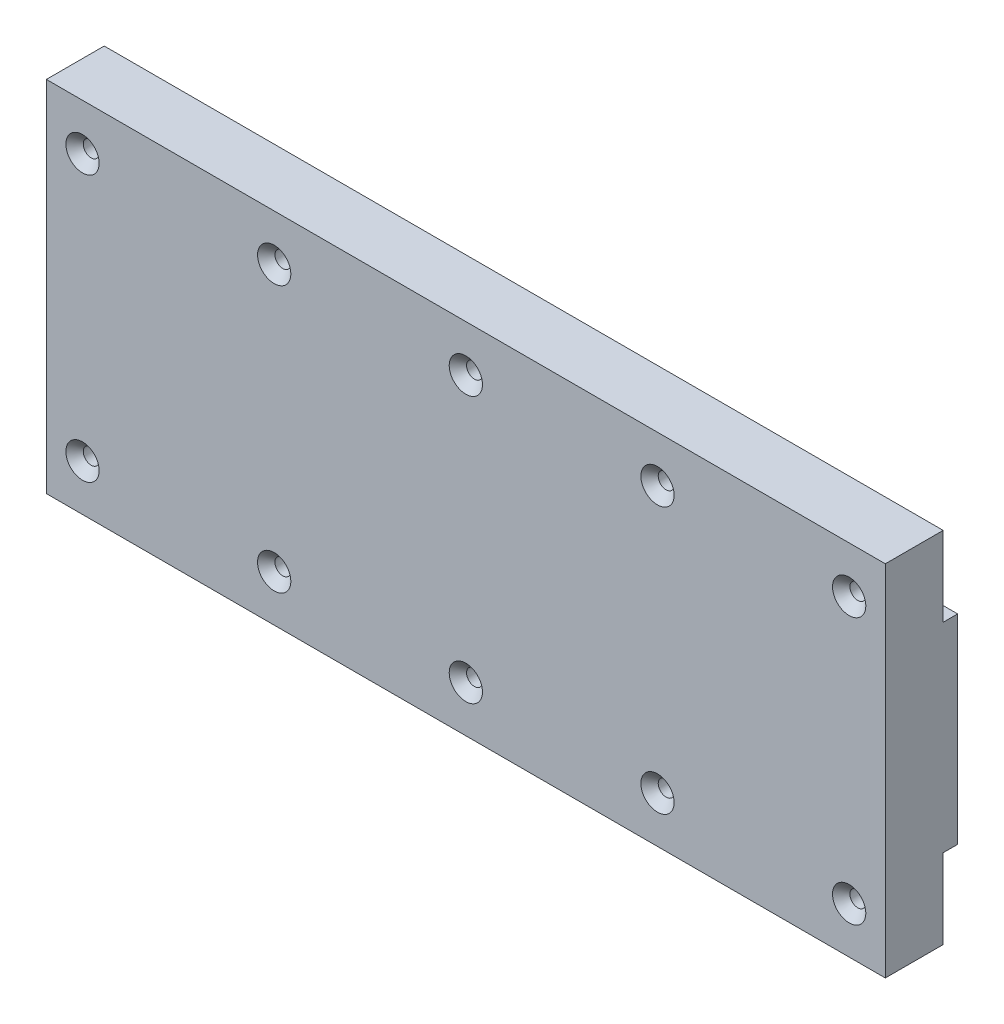
SolidWorks part; units mm, degrees
ref_plane "Front Plane" through (0, 0, 0) normal (0, 0, 1) x (1, 0, 0)
ref_plane "Top Plane" through (0, 0, 0) normal (0, 1, 0) x (1, 0, 0)
ref_plane "Right Plane" through (0, 0, 0) normal (1, 0, 0) x (0, 0, -1)
sketch "Sketch1" plane through (0, 0, 0) normal (1, 0, 0) x (0, 0, -1)
  line L0 (0, -124) -> (-40, -124)
  line L1 (-40, -124) -> (-40, 124)
  line L2 (-40, 124) -> (0, 124)
  line L3 (0, 124) -> (0, 69)
  line L4 (0, 69) -> (10, 69)
  line L5 (10, 69) -> (10, -69)
  line L6 (10, -69) -> (0, -69)
  line L7 (0, -69) -> (0, -124)
  point P8 (-40, 0)
  dimension "D1" = 40
  dimension "D2" = 138
  dimension "D3" = 10
  dimension "D4" = 248
extrude "Boss-Extrude1" add sketch "Sketch1" along normal blind 580
sketch "Sketch2" plane through (0, 0, 40) normal (0, 0, 1) x (1, 0, 0)
  line L0 (0, 0) -> (580, 0) construction
  line L1 (580, 124) -> (580, -124) construction
  line L2 (-65.8414, 92) -> (-65.8414, -92) construction
  line L4 (0, 124) -> (0, -124) construction
  line L5 (290, 124) -> (290, -124) construction
  line L6 (580, 124) -> (0, 124) construction
  line L7 (580, -124) -> (0, -124) construction
  circle A0 centre (25, 92) radius 5.5
  circle A1 centre (157.5, 92) radius 5.5
  circle A2 centre (422.5, 92) radius 5.5
  circle A3 centre (555, 92) radius 5.5
  circle A4 centre (290, 92) radius 5.5
  circle A5 centre (555, -92) radius 5.5
  circle A6 centre (422.5, -92) radius 5.5
  circle A7 centre (290, -92) radius 5.5
  circle A8 centre (157.5, -92) radius 5.5
  circle A9 centre (25, -92) radius 5.5
  point P9 (-65.8414, 0)
  point P10 (0, 0)
  point P17 (25, 92)
  point P18 (157.5, 92)
  point P19 (290, 92)
  point P20 (422.5, 92)
  point P21 (555, 92)
  dimension "D5" = 11
  dimension "D6" = 11
  dimension "D7" = 11
  dimension "D1" = 184
  dimension "D2" = 25
  dimension "D3" = 132.5
  dimension "D4" = 132.5
extrude "Cut-Extrude1" cut sketch "Sketch2" against normal through all
chamfer "Chamfer1" distance 6 angle 45 10 edges at (560.5, -92, 40) (428, -92, 40) (284.5, -92, 40) (152, -92, 40) (19.5, -92, 40) (549.5, 92, 40) (417, 92, 40) (295.5, 92, 40) (163, 92, 40) (30.5, 92, 40)
